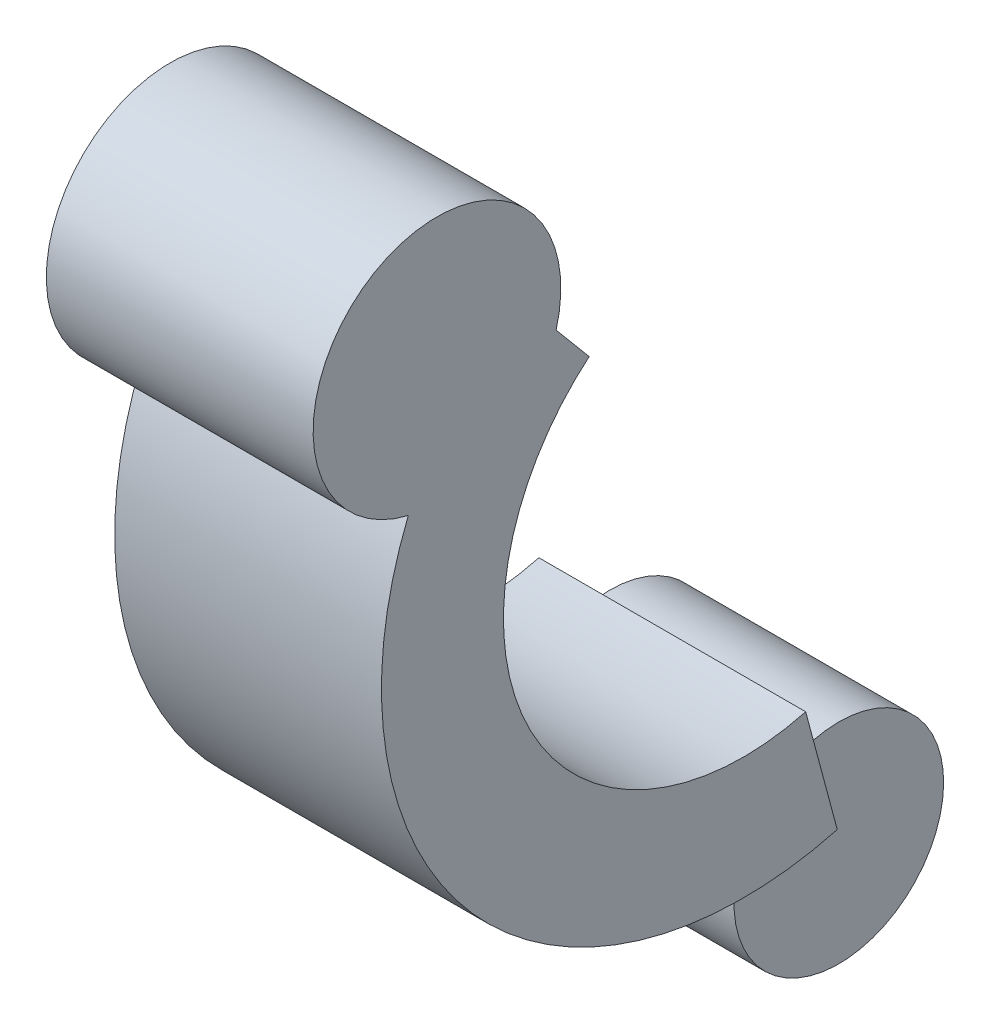
SolidWorks part; units mm, degrees
material "Nylon 101"
ref_plane "Alzado" through (0, 0, 0) normal (0, 0, 1) x (1, 0, 0)
ref_plane "Planta" through (0, 0, 0) normal (0, 1, 0) x (1, 0, 0)
ref_plane "Vista lateral" through (0, 0, 0) normal (1, 0, 0) x (0, 0, -1)
ref_plane "Plane2" through (-7, 0, 0) normal (1, 0, 0) x (0, 0, -1)
sketch "Sketch1" plane through (-7, 0, 0) normal (1, 0, 0) x (0, 0, -1)
  line L0 (4.9176, -18.3526) -> (3.2611, -12.1707)
  line L1 (-8.0991, 9.6522) -> (-12.213, 14.5548)
  arc A0 (-12.213, 14.5548) -> (4.9176, -18.3526) centre (0, 0) ccw
  arc A1 (-8.0991, 9.6522) -> (3.2611, -12.1707) centre (0, 0) ccw
extrude "Gancho_troclear" add sketch "Sketch1" along normal blind 14
sketch "Sketch2" plane through (-7, 0, 0) normal (1, 0, 0) x (0, 0, -1)
  circle A0 centre (-16.0869, 13.4985) radius 6.5
extrude "Olecranon" add sketch "Sketch2" along normal blind 14
ref_plane "Plane4" through (-6, 0, 0) normal (1, 0, 0) x (0, 0, -1)
sketch "Sketch3" plane through (-6, 0, 0) normal (1, 0, 0) x (0, 0, -1)
  circle A0 centre (6, -20) radius 5.5
extrude "Coronoides" add sketch "Sketch3" along normal blind 12
